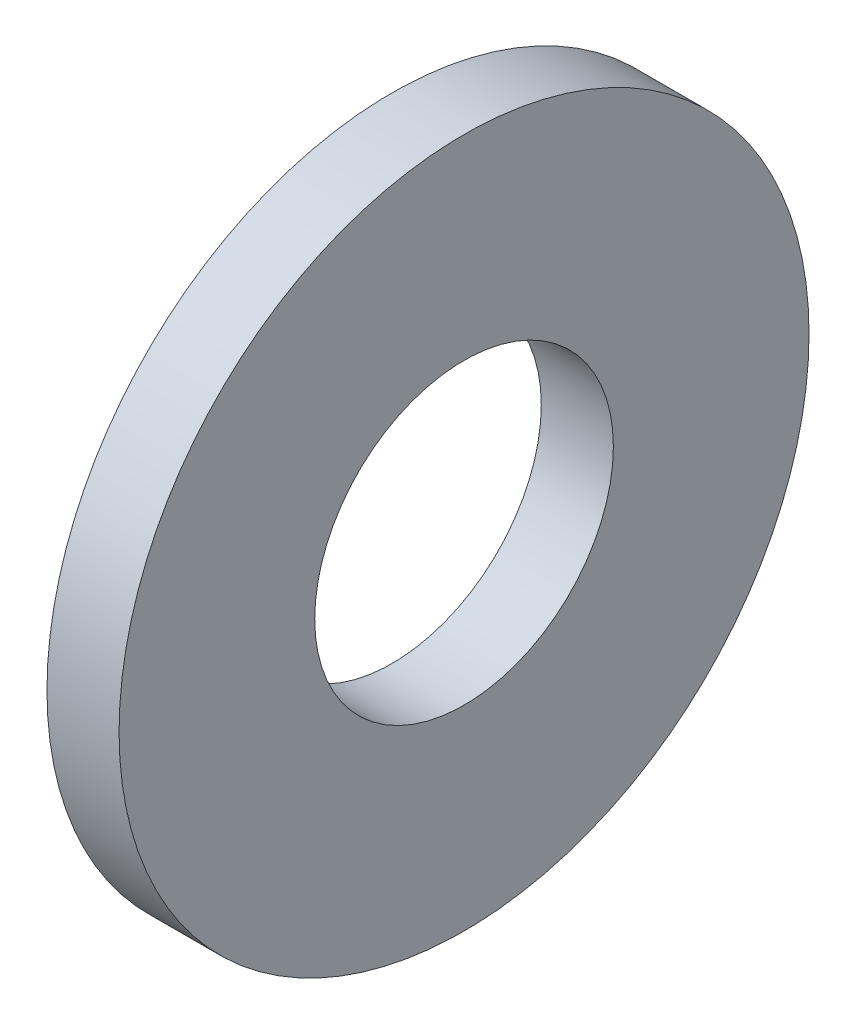
SolidWorks part; units mm, degrees
ref_plane "Plane1" through (0, 0, 0) normal (0, 0, 1) x (1, 0, 0)
ref_plane "Plane2" through (0, 0, 0) normal (0, 1, 0) x (1, 0, 0)
ref_plane "Plane3" through (0, 0, 0) normal (1, 0, 0) x (0, 0, -1)
sketch "Sketch1" plane through (0, 0, 0) normal (0, 0, 1) x (1, 0, 0)
  line L0 (-34.925, 0) -> (9.525, 0) construction
  line L1 (0, 2.5781) -> (0, 5.9563)
  line L2 (0, 5.9563) -> (-1.2446, 5.9563)
  line L3 (-1.2446, 5.9563) -> (-1.2446, 2.5781)
  line L4 (-1.2446, 2.5781) -> (0, 2.5781)
  dimension "Thickness" = 1.2446
  dimension "Inside_dia" = 5.1562
  dimension "Outside_dia" = 11.9126
revolve "Base-Revolve" add sketch "Sketch1" angle 360 about L0
